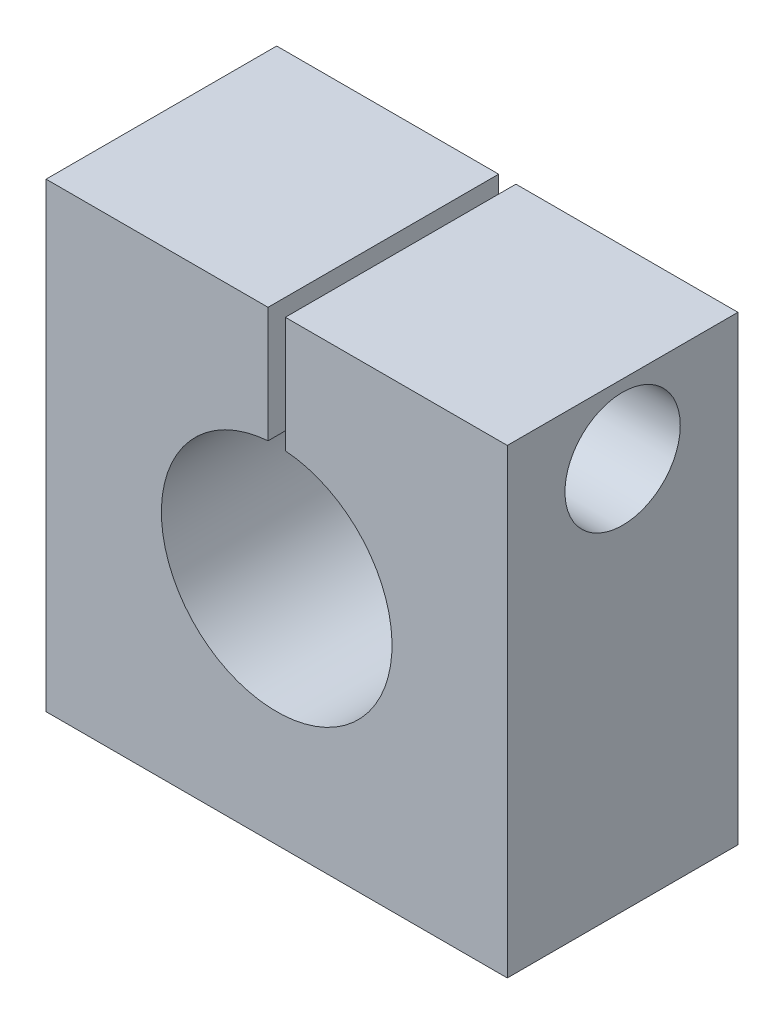
SolidWorks part; units mm, degrees
material "Aleación 1060"
ref_plane "Alzado" through (0, 0, 0) normal (0, 0, 1) x (1, 0, 0)
ref_plane "Planta" through (0, 0, 0) normal (0, 1, 0) x (1, 0, 0)
ref_plane "Vista lateral" through (0, 0, 0) normal (1, 0, 0) x (0, 0, -1)
sketch "Croquis1" plane through (0, 0, 0) normal (0, 0, 1) x (1, 0, 0)
  line L0 (-0.75, 34.9718) -> (-0.75, 45)
  line L1 (20, -45) -> (-20, -45) construction
  line L2 (20, -45) -> (20, 45) construction
  line L3 (20, 45) -> (-20, 45) construction
  line L4 (-20, -45) -> (-20, 45) construction
  line L5 (20, -45) -> (-20, 45) construction
  line L6 (20, 45) -> (-20, -45) construction
  line L7 (0.75, -6.3) -> (-0.75, -6.3) construction
  line L8 (0.75, -6.3) -> (0.75, 56.3) construction
  line L9 (0.75, 56.3) -> (-0.75, 56.3) construction
  line L10 (-0.75, -6.3) -> (-0.75, 56.3) construction
  line L11 (0.75, -6.3) -> (-0.75, 56.3) construction
  line L12 (0.75, 56.3) -> (-0.75, -6.3) construction
  line L13 (-0.75, 45) -> (-20, 45)
  line L14 (-20, 45) -> (-20, -45)
  line L15 (-20, -45) -> (20, -45)
  line L16 (20, -45) -> (20, 45)
  line L17 (20, 45) -> (0.75, 45)
  line L18 (0.75, 45) -> (0.75, 34.9718)
  line L19 (-20, -35) -> (20, -35) construction
  circle A0 centre (0, 25) radius 10 construction
  arc A1 (-0.75, 34.9718) -> (0.75, 34.9718) centre (0, 25) ccw
  circle A2 centre (-10, -35) radius 3
  circle A3 centre (10, -35) radius 3
  point P0 (0, 0)
  dimension "D3" = 25
  dimension "D6" = 20
  dimension "D7" = 20
  dimension "D1" = 90
  dimension "D2" = 40
  dimension "D4" = 62.6
  dimension "D5" = 1.5
  dimension "D8" = 10
extrude "Saliente-Extruir1" add sketch "Croquis1" along normal blind 20 contours A1 L0 L13 L14 L15 L16 L17 L18
sketch "Croquis2" plane through (20, 0, 0) normal (1, 0, 0) x (0, 0, -1)
  line L0 (-20, 45) -> (0, 45) construction
  circle A0 centre (-10, 39) radius 3
  dimension "D1" = 6
extrude "Cortar-Extruir1" cut sketch "Croquis2" against normal blind 30
sketch "Croquis3" plane through (20, 0, 0) normal (1, 0, 0) x (0, 0, -1)
  circle A0 centre (-10, 39) radius 5
extrude "Cortar-Extruir2" cut sketch "Croquis3" against normal blind 10
sketch "Croquis4" plane through (0, 0, 20) normal (0, 0, 1) x (1, 0, 0)
  line L1 (-20, -45) -> (20, -45)
  line L2 (-20, -45) -> (-20, 5)
  line L3 (-20, 5) -> (20, 5)
  line L4 (20, -45) -> (20, 5)
  line L5 (20, -45) -> (20, 45) construction
  arc A1 (-0.75, 34.9718) -> (0.75, 34.9718) centre (0, 25) ccw construction
  point P11 (0, 15)
  dimension "D1" = 10
  dimension "D2" = 40
extrude "Cortar-Extruir3" cut sketch "Croquis4" against normal through all
sketch "Croquis5" plane through (0, 5, 0) normal (0, -1, 0) x (1, 0, 0)
  line L0 (-20, 0) -> (-20, 20) construction
  circle A0 centre (-10, 10) radius 4
  circle A1 centre (10, 10) radius 4
  dimension "D1" = 20
  dimension "D2" = 10
extrude "Cortar-Extruir4" cut sketch "Croquis5" against normal blind 10
